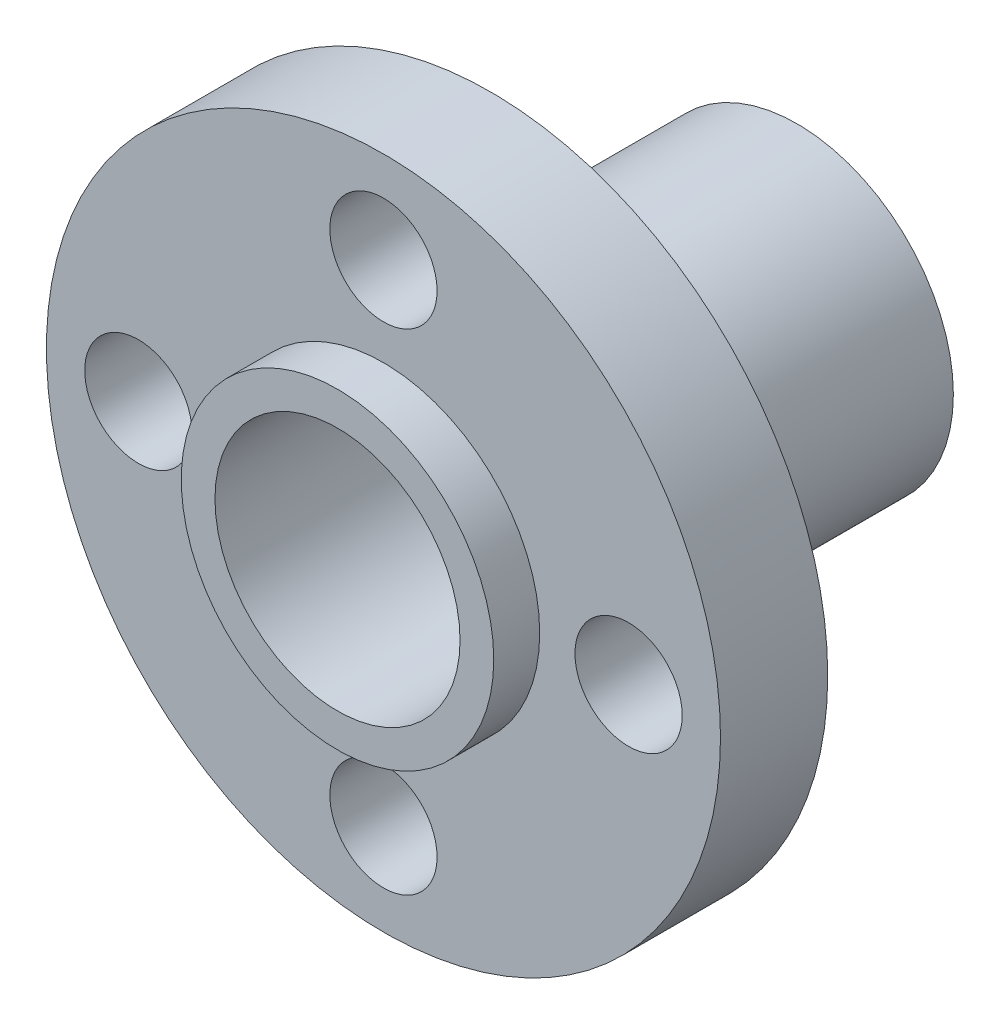
SolidWorks part; units mm, degrees
material "黄铜"
ref_plane "前视基准面" through (0, 0, 0) normal (0, 0, 1) x (1, 0, 0)
ref_plane "上视基准面" through (0, 0, 0) normal (0, 1, 0) x (1, 0, 0)
ref_plane "右视基准面" through (0, 0, 0) normal (1, 0, 0) x (0, 0, -1)
other "Configuration Table"
sketch "草图1" plane through (0, 0, 0) normal (0, 0, 1) x (1, 0, 0)
  circle A0 centre (0, 0) radius 5
  circle A1 centre (0, 0) radius 8 construction
  circle A2 centre (0, 0) radius 11
  circle A3 centre (0, 8) radius 1.75
  circle A4 centre (8, 0) radius 1.75
  circle A5 centre (0, -8) radius 1.75
  circle A6 centre (-8, 0) radius 1.75
  point P16 (0, 0)
  dimension "D1" = 22
  dimension "D2" = 16
  dimension "D3" = 10
  dimension "D4" = 3.5
  dimension "D5" = 4
extrude "凸台-拉伸1" add sketch "草图1" along normal blind 3.5
sketch "草图2" plane through (0, 0, 3.5) normal (0, 0, 1) x (1, 0, 0)
  circle A0 centre (0, 0) radius 5.1
  circle A1 centre (0, 0) radius 4
  dimension "D1" = 8
  dimension "D2" = 10.2
extrude "凸台-拉伸2" add sketch "草图2" along normal blind 1.5 and the other way blind 13.5
